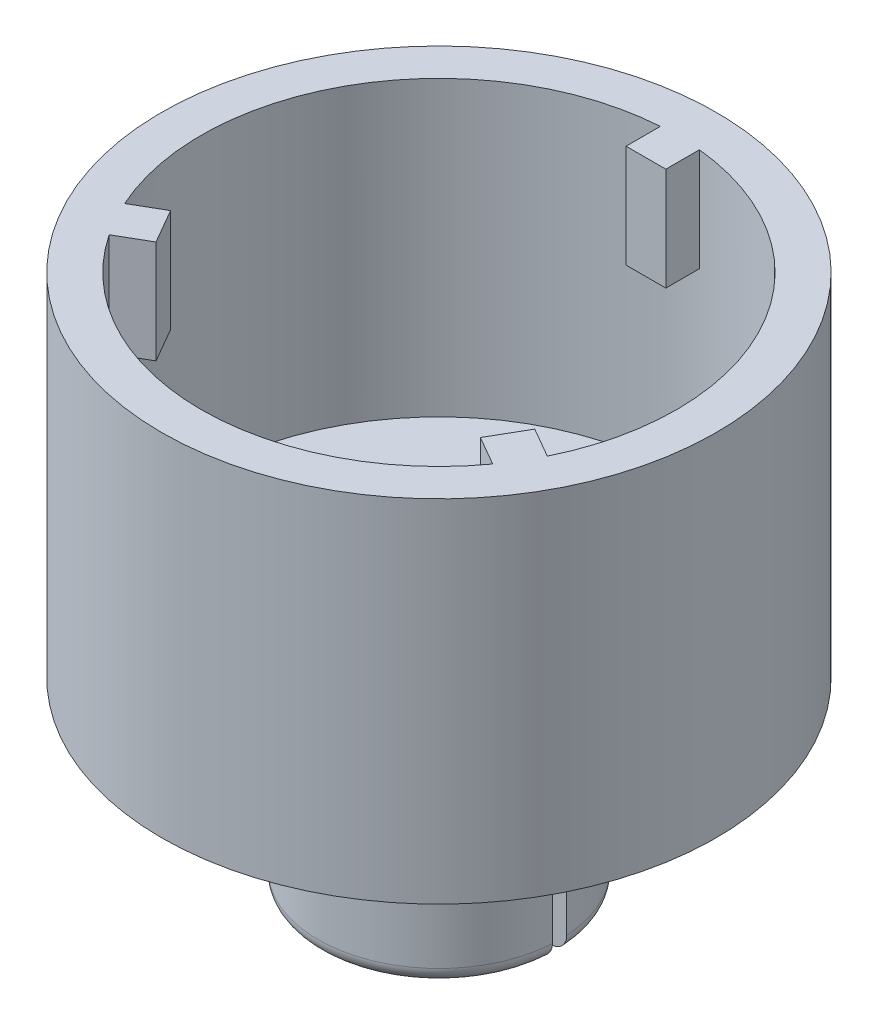
SolidWorks part; units mm, degrees
ref_plane "Front Plane" through (0, 0, 0) normal (0, 0, 1) x (1, 0, 0)
ref_plane "Top Plane" through (0, 0, 0) normal (0, 1, 0) x (1, 0, 0)
ref_plane "Right Plane" through (0, 0, 0) normal (1, 0, 0) x (0, 0, -1)
sketch "Sketch1" plane through (0, 0, 0) normal (0, 1, 0) x (1, 0, 0)
  circle A0 centre (0, 0) radius 35
  dimension "D1" = 70
extrude "Boss-Extrude1" add sketch "Sketch1" along normal blind 44.3
sketch "Sketch2" plane through (0, 44.3, 0) normal (0, 1, 0) x (1, 0, 0)
  circle A0 centre (0, 0) radius 30
  dimension "D1" = 60
extrude "Cut-Extrude1" cut sketch "Sketch2" against normal blind 37
sketch "Sketch3" plane through (0, 0, 0) normal (0, -1, 0) x (1, 0, 0)
  circle A0 centre (0, 0) radius 19.5
  dimension "D1" = 39
extrude "Boss-Extrude2" add sketch "Sketch3" along normal blind 7
sketch "Sketch4" plane through (0, -7, 0) normal (0, -1, 0) x (1, 0, 0)
  circle A0 centre (0, 0) radius 15.25
  dimension "D1" = 30.5
extrude "Boss-Extrude3" add sketch "Sketch4" along normal blind 16
fillet "Fillet1" radius 5 1 edges at (0, 0, -19.5)
sketch "Sketch5" plane through (0, 44.3, 0) normal (0, 1, 0) x (1, 0, 0)
  line L0 (-1.9905, 29.9339) -> (-1.9905, 25.6053)
  line L1 (-1.9905, 25.6053) -> (3.0302, 25.6053)
  line L2 (3.0302, 25.6053) -> (3.0302, 29.8466)
  line L3 (26.9188, -13.2431) -> (23.1701, -11.0788)
  line L4 (23.1701, -11.0788) -> (20.6597, -15.4269)
  line L5 (20.6597, -15.4269) -> (24.3328, -17.5475)
  line L6 (-24.9282, -16.6908) -> (-21.1796, -14.5265)
  line L7 (-21.1796, -14.5265) -> (-23.69, -10.1784)
  line L8 (-23.69, -10.1784) -> (-27.363, -12.299)
  circle A0 centre (0, 0) radius 30 construction
  arc A1 (24.3328, -17.5475) -> (26.9188, -13.2431) centre (0, 0) ccw
  circle A2 centre (0, 0) radius 30
  arc A3 (3.0302, 29.8466) -> (-1.9905, 29.9339) centre (0, 0) ccw
  arc A4 (-27.363, -12.299) -> (-24.9282, -16.6908) centre (0, 0) ccw
  point P19 (0, 0)
  dimension "D1" = 0
  dimension "D2" = 3
extrude "Boss-Extrude4" add sketch "Sketch5" against normal blind 13
sketch "Sketch7" plane through (0, -23, 0) normal (0, -1, 0) x (1, 0, 0)
  line L1 (33.0968, 0.9034) -> (-33.0968, 0.9034)
  line L2 (33.0968, 0.9034) -> (33.0968, -0.9034)
  line L3 (33.0968, -0.9034) -> (-33.0968, -0.9034)
  line L4 (-33.0968, 0.9034) -> (-33.0968, -0.9034)
  line L5 (33.0968, 0.9034) -> (-33.0968, -0.9034) construction
  line L6 (33.0968, -0.9034) -> (-33.0968, 0.9034) construction
  point P0 (0, 0)
extrude "Cut-Extrude2" cut sketch "Sketch7" against normal up to surface (16 mm away) up to face at (0, -7, -15.25)
fillet "Fillet2" radius 2 2 edges at (0, -23, 15.25) (0, -23, -15.25)
sketch "Sketch8" plane through (0, 7.3, 0) normal (0, 1, 0) x (1, 0, 0)
  circle A0 centre (0, 0) radius 10.3601
